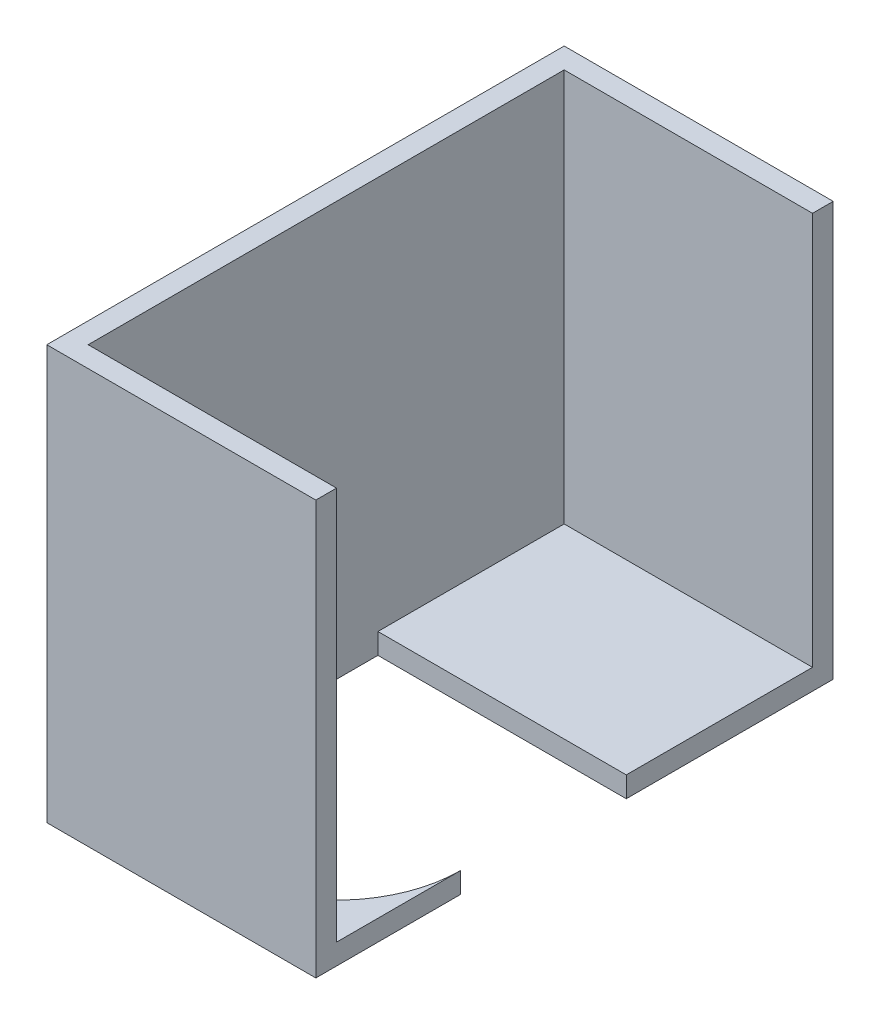
SolidWorks part; units mm, degrees
ref_plane "정면" through (0, 0, 0) normal (0, 0, 1) x (1, 0, 0)
ref_plane "윗면" through (0, 0, 0) normal (0, 1, 0) x (1, 0, 0)
ref_plane "우측면" through (0, 0, 0) normal (1, 0, 0) x (0, 0, -1)
sketch "스케치15" plane through (0, 0, 0) normal (0, 1, 0) x (1, 0, 0)
  line L1 (-6, -12.5) -> (7, -12.5)
  line L2 (-6, -12.5) -> (-6, 12.5)
  line L3 (-6, 12.5) -> (7, 12.5)
  line L4 (7, -12.5) -> (7, 12.5)
  dimension "D1" = 13
  dimension "D2" = 25
extrude "보스-돌출4" add sketch "스케치15" along normal blind 20
sketch "스케치16" plane through (0, 0, 0) normal (0, 1, 0) x (1, 0, 0)
  line L0 (7, -12.5) -> (7, 12.5) construction
  line L1 (-5, 11.5) -> (7, 11.5)
  line L2 (-5, 11.5) -> (-5, -11.5)
  line L3 (-5, -11.5) -> (7, -11.5)
  line L4 (7, 11.5) -> (7, -11.5)
  line L5 (-6, -12.5) -> (7, -12.5) construction
  dimension "D1" = 12
  dimension "D2" = 23
  dimension "D3" = 1
extrude "컷-돌출47" cut sketch "스케치16" along normal through all from offset 1
sketch "스케치17" plane through (0, 0, 0) normal (0, 1, 0) x (1, 0, 0)
  line L0 (-5, -11.5) -> (7, -11.5) construction
  line L1 (-5, 11.5) -> (-5, -11.5) construction
  line L3 (-5, 2.5) -> (7, 2.5)
  line L4 (-5, 2.5) -> (-5, -5.5)
  line L6 (7, 2.5) -> (7, -5.5)
  arc A0 (-5, -5.5) -> (7, -5.5) centre (1, -5.5) ccw
  dimension "D1" = 12
  dimension "D2" = 12
  dimension "D3" = 8
extrude "컷-돌출48" cut sketch "스케치17" along normal through all
